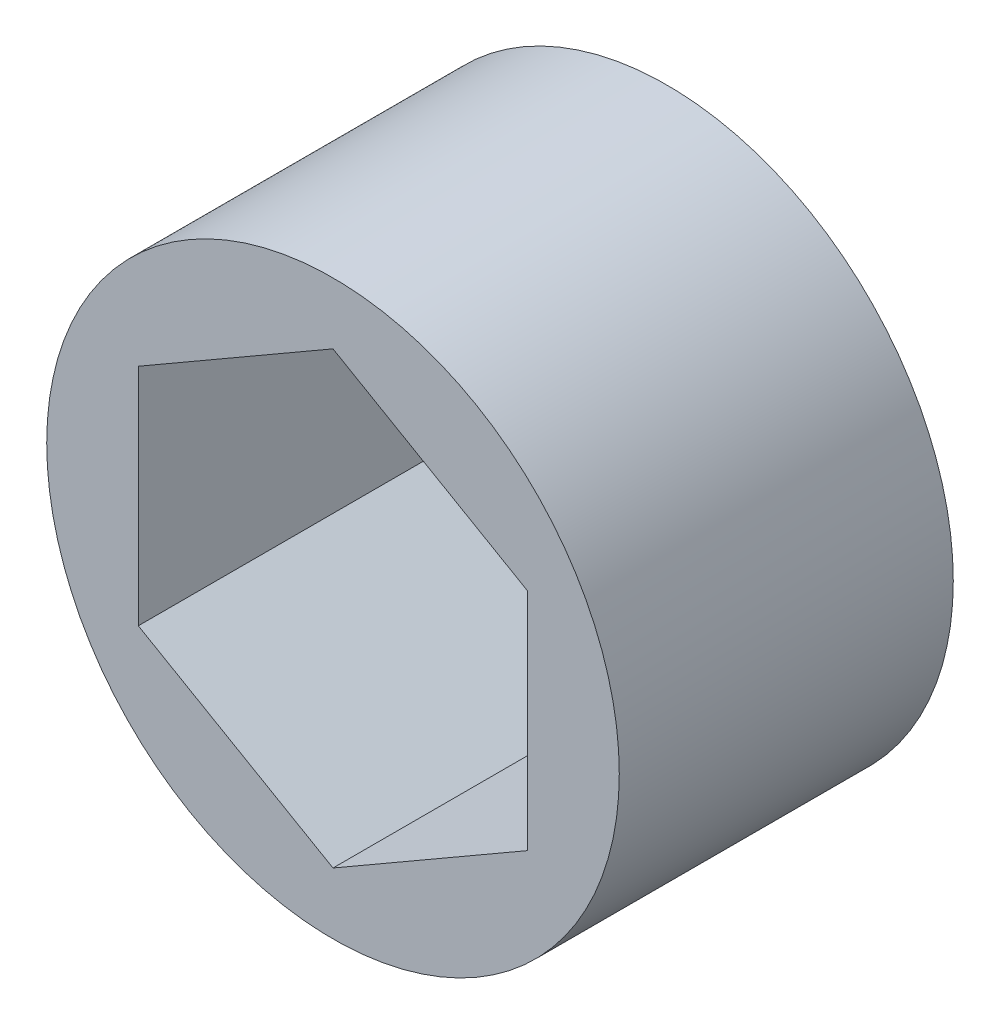
SolidWorks part; units mm, degrees
material "PET"
ref_plane "Front Plane" through (0, 0, 0) normal (0, 0, 1) x (1, 0, 0)
ref_plane "Top Plane" through (0, 0, 0) normal (0, 1, 0) x (1, 0, 0)
ref_plane "Right Plane" through (0, 0, 0) normal (1, 0, 0) x (0, 0, -1)
sketch "Sketch1" plane through (0, 0, 0) normal (0, 0, 1) x (1, 0, 0)
  line L1 (0, 7.479) -> (-6.477, 3.7395)
  line L2 (-6.477, 3.7395) -> (-6.477, -3.7395)
  line L3 (-6.477, -3.7395) -> (0, -7.479)
  line L4 (0, -7.479) -> (6.477, -3.7395)
  line L5 (6.477, -3.7395) -> (6.477, 3.7395)
  line L6 (6.477, 3.7395) -> (0, 7.479)
  circle A0 centre (0, 0) radius 6.477 construction
  circle A1 centre (0, 0) radius 9.525
  dimension "D1" = 12.954
  dimension "D2" = 19.05
extrude "Boss-Extrude1" add sketch "Sketch1" along normal mid plane 11.1125
